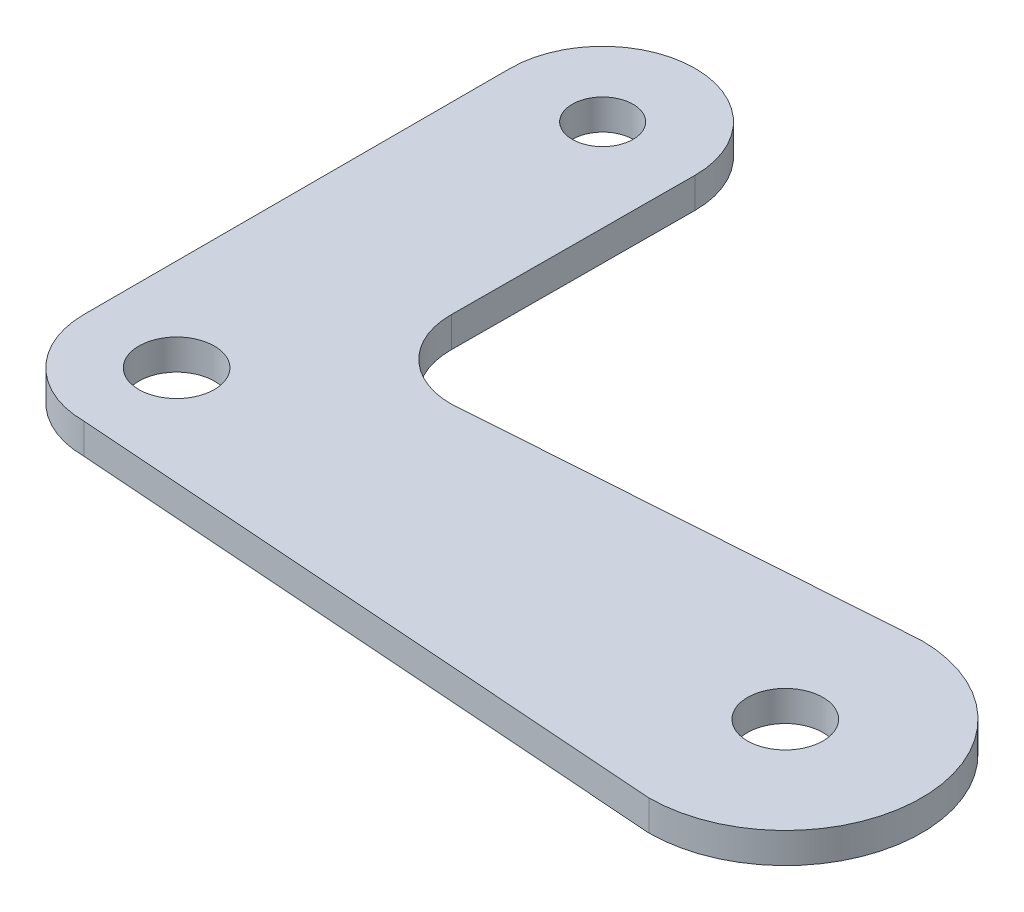
SolidWorks part; units mm, degrees
ref_plane "Front Plane" through (0, 0, 0) normal (0, 0, 1) x (1, 0, 0)
ref_plane "Top Plane" through (0, 0, 0) normal (0, 1, 0) x (1, 0, 0)
ref_plane "Right Plane" through (0, 0, 0) normal (1, 0, 0) x (0, 0, -1)
sketch "Sketch1" plane through (0, 0, 0) normal (0, 1, 0) x (1, 0, 0)
  line L0 (-66.7437, 21.7008) -> (-66.7437, -22.7492)
  line L1 (-57.0917, -32.4012) -> (6.4083, -36.9732)
  line L2 (6.4083, -8.5252) -> (-39.5657, -11.7002)
  line L3 (-47.4397, 21.7008) -> (-47.5667, -3.6992)
  circle A0 centre (-57.0917, 21.7008) radius 3.175
  circle A1 centre (-57.0917, -22.7492) radius 3.937
  circle A2 centre (6.4083, -22.7492) radius 3.937
  arc A3 (4.3706, -36.8265) -> (4.4529, -8.6603) centre (6.4083, -22.7492) ccw
  arc A4 (-66.7437, -22.7492) -> (-57.0917, -32.4012) centre (-57.0917, -22.7492) ccw
  arc A5 (-47.4402, 21.6042) -> (-66.7437, 21.7008) centre (-57.0917, 21.7008) ccw
  arc A6 (-47.5663, -3.6192) -> (-38.4659, -11.6243) centre (-39.5657, -3.6992) ccw
  point P19 (-39.5657, -11.7002)
  point P20 (0, 0)
  point P21 (6.4083, -8.5252)
  point P22 (6.4083, -36.9732)
  point P23 (-57.0917, -32.4012)
  point P24 (-66.7437, -22.7492)
  dimension "D1" = 44.45
  dimension "D2" = 19.304
  dimension "D3" = 6.35
  dimension "D4" = 7.874
  dimension "D5" = 28.448
  dimension "D6" = 16.002
  dimension "D7" = 63.5
  dimension "D8" = 19.05
  dimension "D9" = 17.526
extrude "Boss-Extrude1" add sketch "Sketch1" against normal blind 3.175 contours A6 L3 A5 L0 A4 L1 A3 L2 A2 A1 A0
